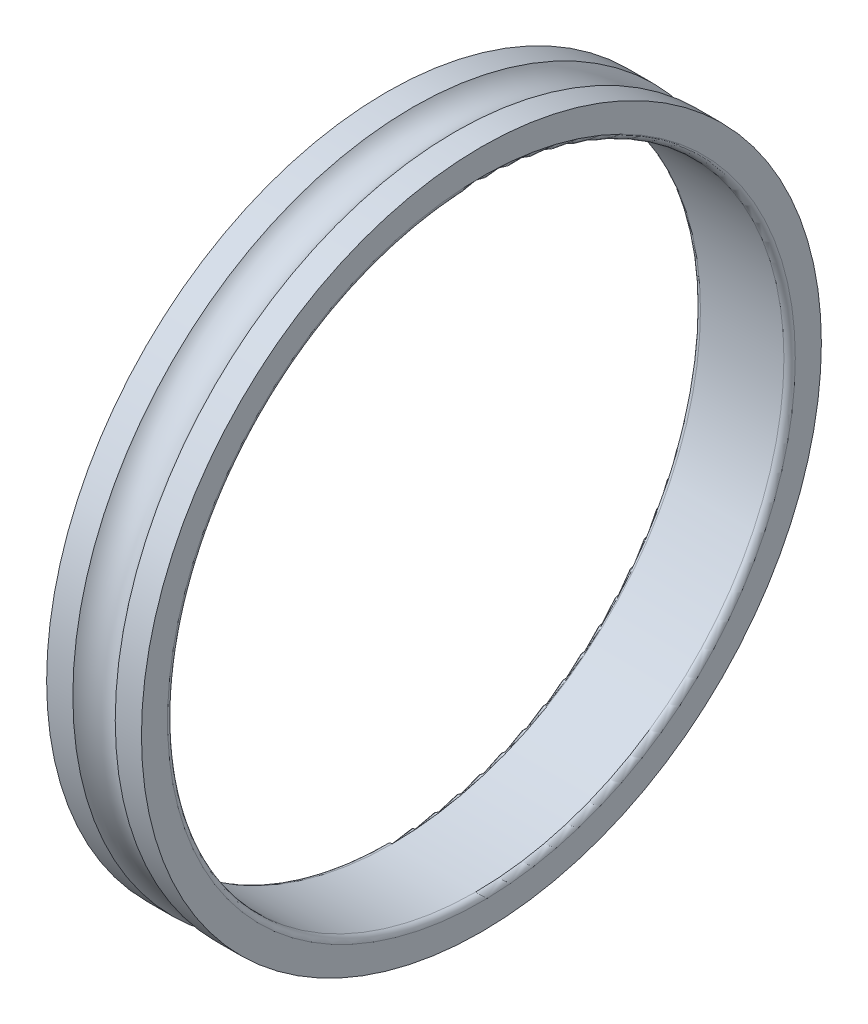
SolidWorks part; units mm, degrees
material "1.2312 (40CrMnMoS8-6)"
ref_plane "Front Plane" through (0, 0, 0) normal (0, 0, 1) x (1, 0, 0)
ref_plane "Top Plane" through (0, 0, 0) normal (0, 1, 0) x (1, 0, 0)
ref_plane "Right Plane" through (0, 0, 0) normal (1, 0, 0) x (0, 0, -1)
sketch "草图1" plane through (0, 0, 0) normal (0, 0, 1) x (1, 0, 0)
  line L0 (0, 35.85) -> (0, 33.1)
  line L1 (0.6, 32.5) -> (9.4, 32.5)
  line L2 (10, 33.1) -> (10, 35.85)
  line L3 (10, 35.85) -> (7.2349, 35.85)
  line L4 (2.7651, 35.85) -> (0, 35.85)
  line L5 (-0.0013, 0) -> (10.0013, 0) construction
  arc A0 (0, 33.1) -> (0.6, 32.5) centre (0.6, 33.1) ccw
  arc A1 (9.4, 32.5) -> (10, 33.1) centre (9.4, 33.1) ccw
  arc A2 (7.2349, 35.85) -> (2.7651, 35.85) centre (5, 37.5) cw
revolve "旋转1" add sketch "草图1" angle 360 about L5
